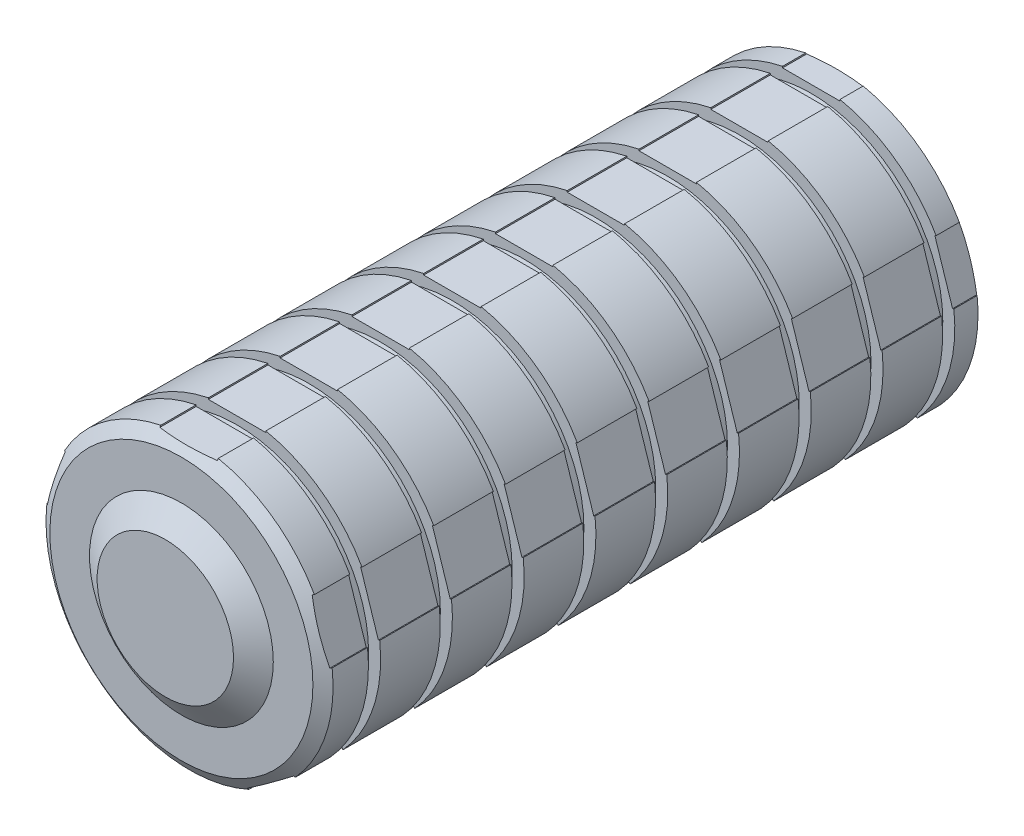
SolidWorks part; units mm, degrees
ref_plane "前视基准面" through (0, 0, 0) normal (0, 0, 1) x (1, 0, 0)
ref_plane "上视基准面" through (0, 0, 0) normal (0, 1, 0) x (1, 0, 0)
ref_plane "右视基准面" through (0, 0, 0) normal (1, 0, 0) x (0, 0, -1)
sketch "草图1" plane through (0, 0, 0) normal (0, 0, 1) x (1, 0, 0)
  circle A0 centre (0, 0) radius 2000
extrude "凸台-拉伸1" add sketch "草图1" along normal blind 10000
sketch "草图2" plane through (0, 0, 0) normal (0, 1, 0) x (1, 0, 0)
  line L0 (488.2239, 101.5856) -> (488.2239, -266.3512)
  line L1 (488.2239, -266.3512) -> (842.0093, -266.3512)
  line L2 (842.0093, -266.3512) -> (1280.7032, -563.5309)
  line L3 (1280.7032, -563.5309) -> (1832.6084, -563.5309)
  line L4 (1832.6084, -563.5309) -> (2350.7282, -914.5153)
  line L6 (3073.9057, 313.8569) -> (488.2239, 313.8569)
  line L7 (488.2239, 313.8569) -> (488.2239, 101.5856)
  line L8 (3073.9057, -1000) -> (1832.6084, -1000)
  line L9 (1832.6084, -1000) -> (1832.6084, -1169.817)
  line L10 (1832.6084, -1169.817) -> (3073.9057, -1169.817)
  line L11 (3073.9057, -1169.817) -> (3073.9057, -1000)
  line L12 (2350.7282, -914.5153) -> (3073.9057, -914.5153)
  line L13 (3073.9057, -914.5153) -> (3073.9057, 313.8569)
  line L14 (3073.9057, -2000) -> (1832.6084, -2000)
  line L15 (1832.6084, -2169.817) -> (3073.9057, -2169.817)
  line L16 (1832.6084, -2000) -> (1832.6084, -2169.817)
  line L17 (3073.9057, -2169.817) -> (3073.9057, -2000)
  line L18 (3073.9057, -3000) -> (1832.6084, -3000)
  line L19 (1832.6084, -3169.817) -> (3073.9057, -3169.817)
  line L20 (1832.6084, -3000) -> (1832.6084, -3169.817)
  line L21 (3073.9057, -3169.817) -> (3073.9057, -3000)
  line L22 (3073.9057, -4000) -> (1832.6084, -4000)
  line L23 (1832.6084, -4169.817) -> (3073.9057, -4169.817)
  line L24 (1832.6084, -4000) -> (1832.6084, -4169.817)
  line L25 (3073.9057, -4169.817) -> (3073.9057, -4000)
  line L26 (3073.9057, -5000) -> (1832.6084, -5000)
  line L27 (1832.6084, -5169.817) -> (3073.9057, -5169.817)
  line L28 (1832.6084, -5000) -> (1832.6084, -5169.817)
  line L29 (3073.9057, -5169.817) -> (3073.9057, -5000)
  line L30 (3073.9057, -6000) -> (1832.6084, -6000)
  line L31 (1832.6084, -6169.817) -> (3073.9057, -6169.817)
  line L32 (1832.6084, -6000) -> (1832.6084, -6169.817)
  line L33 (3073.9057, -6169.817) -> (3073.9057, -6000)
  line L34 (3073.9057, -7000) -> (1832.6084, -7000)
  line L35 (1832.6084, -7169.817) -> (3073.9057, -7169.817)
  line L36 (1832.6084, -7000) -> (1832.6084, -7169.817)
  line L37 (3073.9057, -7169.817) -> (3073.9057, -7000)
  line L38 (3073.9057, -8000) -> (1832.6084, -8000)
  line L39 (1832.6084, -8169.817) -> (3073.9057, -8169.817)
  line L40 (1832.6084, -8000) -> (1832.6084, -8169.817)
  line L41 (3073.9057, -8169.817) -> (3073.9057, -8000)
  line L42 (3073.9057, -9000) -> (1832.6084, -9000)
  line L43 (1832.6084, -9169.817) -> (3073.9057, -9169.817)
  line L44 (1832.6084, -9000) -> (1832.6084, -9169.817)
  line L45 (3073.9057, -9169.817) -> (3073.9057, -9000)
  line L46 (1832.6084, -9776.1031) -> (2350.7282, -9425.1187)
  line L47 (1280.7032, -9776.1031) -> (1832.6084, -9776.1031)
  line L48 (842.0093, -10073.2828) -> (1280.7032, -9776.1031)
  line L49 (488.2239, -10073.2828) -> (842.0093, -10073.2828)
  line L50 (488.2239, -10441.2196) -> (488.2239, -10073.2828)
  line L51 (488.2239, -10653.4909) -> (488.2239, -10441.2196)
  line L52 (3073.9057, -10653.4909) -> (488.2239, -10653.4909)
  line L53 (3073.9057, -9425.1187) -> (3073.9057, -10653.4909)
  line L54 (2350.7282, -9425.1187) -> (3073.9057, -9425.1187)
  dimension "D1" = 1000
  dimension "D2" = 9
ref_plane "基准面4" through (0, 0, 5000) normal (0, 0, -1) x (-1, 0, 0)
ref_axis "基准轴1" through (0, 0, 10000) along (0, 0, -1)
revolve "切除-旋转2" cut sketch "草图2" angle 360 about axis through (0, 0, 10000) along (0, 0, -1)
sketch "草图4" plane through (0, 0, 0) normal (0, 0, 1) x (1, 0, 0)
  line L0 (-400, 1940) -> (400, 1940)
  line L1 (400, 1940) -> (400, 2500)
  line L2 (400, 2500) -> (-400, 2500)
  line L3 (-400, 2500) -> (-400, 1940)
  line L4 (2254.0345, 1152.9651) -> (1721.4428, 979.9156)
  line L5 (1721.4428, 979.9156) -> (1968.6564, 219.0704)
  line L6 (1968.6564, 219.0704) -> (2501.2481, 392.1199)
  line L7 (2501.2481, 392.1199) -> (2254.0345, 1152.9651)
  line L8 (1793.0699, -1787.4284) -> (1463.9102, -1334.3789)
  line L9 (1463.9102, -1334.3789) -> (816.6966, -1804.6071)
  line L10 (816.6966, -1804.6071) -> (1145.8563, -2257.6566)
  line L11 (1145.8563, -2257.6566) -> (1793.0699, -1787.4284)
  line L12 (-1145.8563, -2257.6566) -> (-816.6966, -1804.6071)
  line L13 (-816.6966, -1804.6071) -> (-1463.9102, -1334.3789)
  line L14 (-1463.9102, -1334.3789) -> (-1793.0699, -1787.4284)
  line L15 (-1793.0699, -1787.4284) -> (-1145.8563, -2257.6566)
  line L16 (-2501.2481, 392.1199) -> (-1968.6564, 219.0704)
  line L17 (-1968.6564, 219.0704) -> (-1721.4428, 979.9156)
  line L18 (-1721.4428, 979.9156) -> (-2254.0345, 1152.9651)
  line L19 (-2254.0345, 1152.9651) -> (-2501.2481, 392.1199)
  point P23 (0, 0)
  dimension "D1" = 400
  dimension "D2" = 400
  dimension "D3" = 2500
  dimension "D4" = 1940
  dimension "D5" = 5
extrude "切除-拉伸1" cut sketch "草图4" along normal blind 10000
